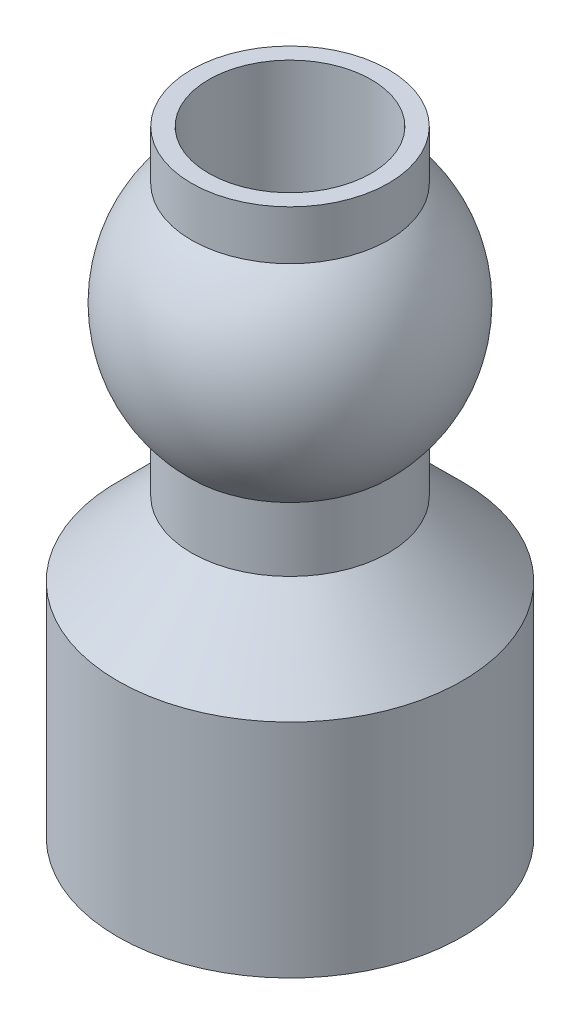
SolidWorks part; units mm, degrees
ref_plane "Front Plane" through (0, 0, 0) normal (0, 0, 1) x (1, 0, 0)
ref_plane "Top Plane" through (0, 0, 0) normal (0, 1, 0) x (1, 0, 0)
ref_plane "Right Plane" through (0, 0, 0) normal (1, 0, 0) x (0, 0, -1)
sketch "Sketch1" plane through (0, 0, 0) normal (0, 0, 1) x (1, 0, 0)
  line L0 (0, 9.8166) -> (0, -11.1633) construction
  line L1 (0, 6.25) -> (0, -6.25)
  line L2 (0, -6.25) -> (3.5, -6.25)
  line L3 (3.5, -6.25) -> (3.5, -1.75)
  line L4 (3.5, -1.75) -> (2, -0.25)
  line L5 (2, -0.25) -> (2, 1.05)
  line L6 (2, 6.25) -> (0, 6.25)
  line L7 (2, 5.25) -> (2, 6.25)
  arc A0 (2, 5.25) -> (2, 1.05) centre (0, 3.15) cw
  point P12 (2, 5.25)
  dimension "D6" = 2.9
  dimension "D1" = 12.5
  dimension "D2" = 4.5
  dimension "D3" = 6.5
  dimension "D4" = 3.5
  dimension "D5" = 2
  dimension "D7" = 1
revolve "Revolve1" add sketch "Sketch1" angle 360 about L0
sketch "Sketch2" plane through (0, 6.25, 0) normal (0, 1, 0) x (1, 0, 0)
  circle A0 centre (0, 0) radius 1.65
  dimension "D1" = 3.3
extrude "Cut-Extrude1" cut sketch "Sketch2" against normal blind 12.5
sketch "Sketch3" plane through (0, 0, 0) normal (1, 0, 0) x (0, 0, -1)
  line L3 (0, 3.15) -> (0, -10.6911) construction
